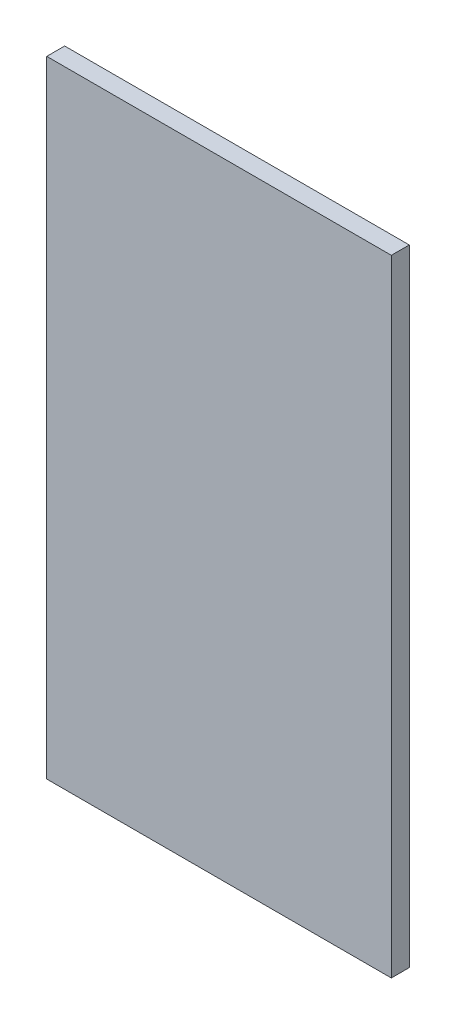
SolidWorks part; units mm, degrees
material "Стекло"
ref_plane "Спереди" through (0, 0, 0) normal (0, 0, 1) x (1, 0, 0)
ref_plane "Сверху" through (0, 0, 0) normal (0, 1, 0) x (1, 0, 0)
ref_plane "Справа" through (0, 0, 0) normal (1, 0, 0) x (0, 0, -1)
sketch "Эскиз1" plane through (0, 0, 0) normal (0, 0, 1) x (1, 0, 0)
  line L1 (490, -890) -> (-490, -890)
  line L2 (490, -890) -> (490, 890)
  line L3 (490, 890) -> (-490, 890)
  line L4 (-490, -890) -> (-490, 890)
  line L5 (490, -890) -> (-490, 890) construction
  line L6 (490, 890) -> (-490, -890) construction
  point P0 (0, 0)
extrude "Бобышка-Вытянуть1" add sketch "Эскиз1" along normal mid plane 51
sketch "Эскиз2" plane through (0, 0, 25.5) normal (0, 0, 1) x (1, 0, 0)
  line L0 (490, -890) -> (490, 890) construction
  line L1 (440, -840) -> (-440, -840) construction
  line L2 (440, -840) -> (440, 840) construction
  line L3 (440, 840) -> (-440, 840) construction
  line L4 (-440, -840) -> (-440, 840) construction
  line L5 (440, -840) -> (-440, 840) construction
  line L6 (440, 840) -> (-440, -840) construction
  point P0 (0, 0)
  dimension "D1" = 50
  dimension "D2" = 50
equation "\"Длина\"= \"D2@Эскиз1@Стеклопакет 1780х980-3.Part@Стеклопакет с подушками-2.Assembly\""
equation "\"Ширина\"= \"D1@Эскиз1@Стеклопакет 1780х980-3.Part@Стеклопакет с подушками-2.Assembly\""
